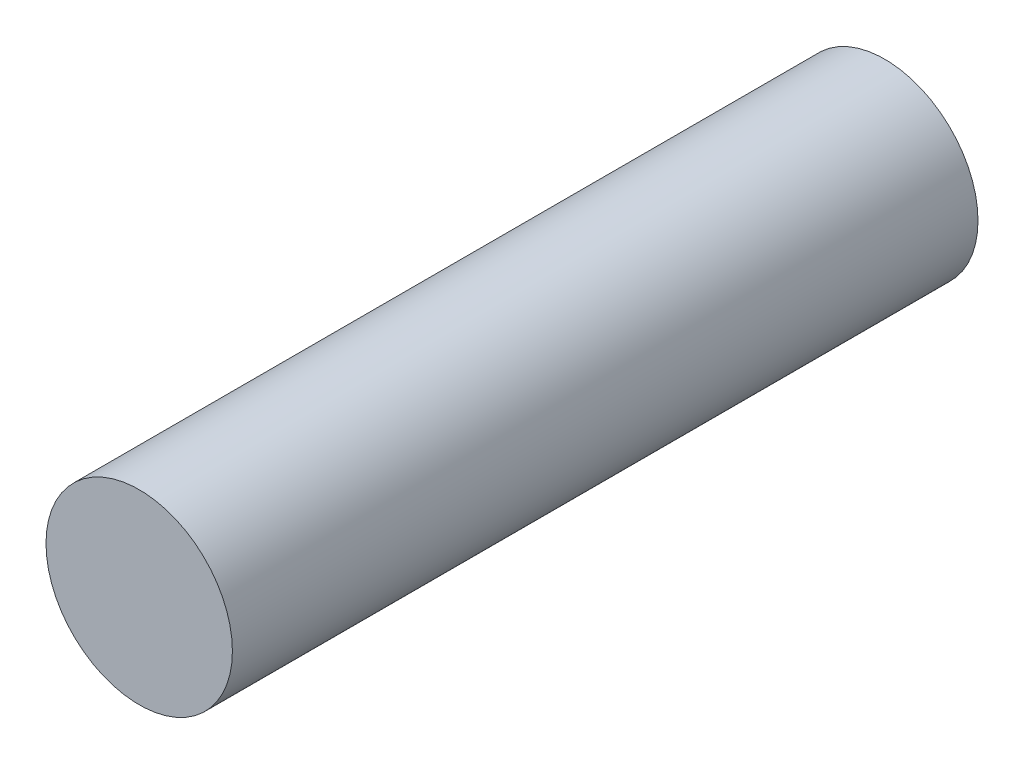
SolidWorks part; units mm, degrees
ref_plane "Front Plane" through (0, 0, 0) normal (0, 0, 1) x (1, 0, 0)
ref_plane "Top Plane" through (0, 0, 0) normal (0, 1, 0) x (1, 0, 0)
ref_plane "Right Plane" through (0, 0, 0) normal (1, 0, 0) x (0, 0, -1)
sketch "Sketch1" plane through (0, 0, 0) normal (0, 0, 1) x (1, 0, 0)
  circle A0 centre (0, 0) radius 50
  dimension "D1" = 100
extrude "Boss-Extrude1" add sketch "Sketch1" along normal blind 400
